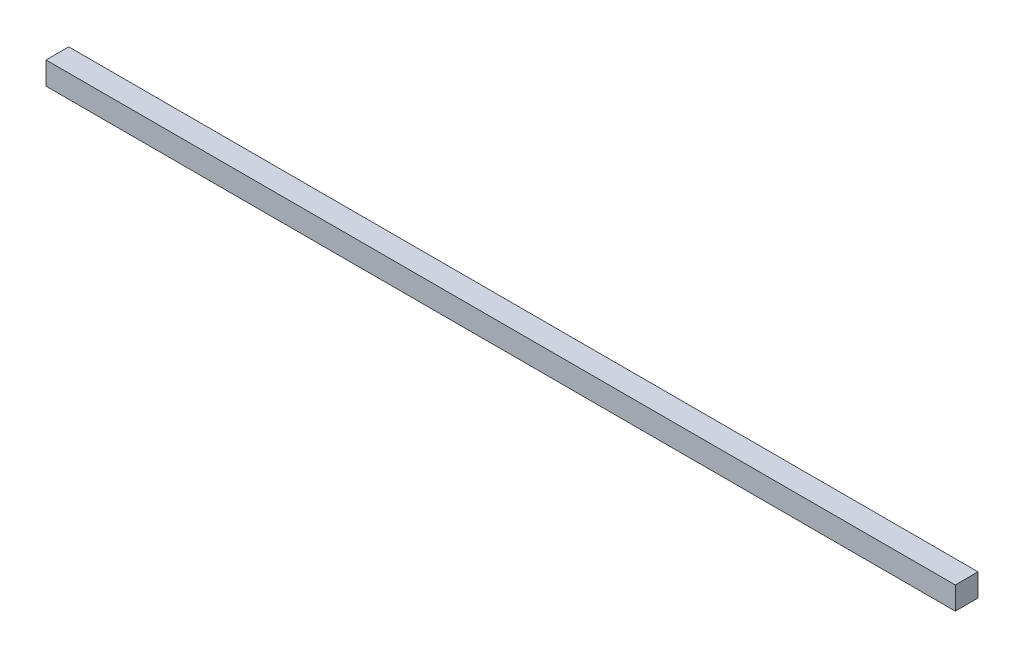
SolidWorks part; units mm, degrees
ref_plane "Front Plane" through (0, 0, 0) normal (0, 0, 1) x (1, 0, 0)
ref_plane "Top Plane" through (0, 0, 0) normal (0, 1, 0) x (1, 0, 0)
ref_plane "Right Plane" through (0, 0, 0) normal (1, 0, 0) x (0, 0, -1)
sketch "Sketch1" plane through (0, 0, 0) normal (0, 1, 0) x (1, 0, 0)
  line L1 (400, -10) -> (0, -10)
  line L2 (400, -10) -> (400, 0)
  line L3 (400, 0) -> (0, 0)
  line L4 (0, -10) -> (0, 0)
  line L5 (400, -10) -> (0, 0) construction
  line L6 (400, 0) -> (0, -10) construction
  point P0 (200, -5)
  dimension "D1" = 400
  dimension "D2" = 10
  dimension "D3" = 0
extrude "Boss-Extrude1" add sketch "Sketch1" along normal blind 10
